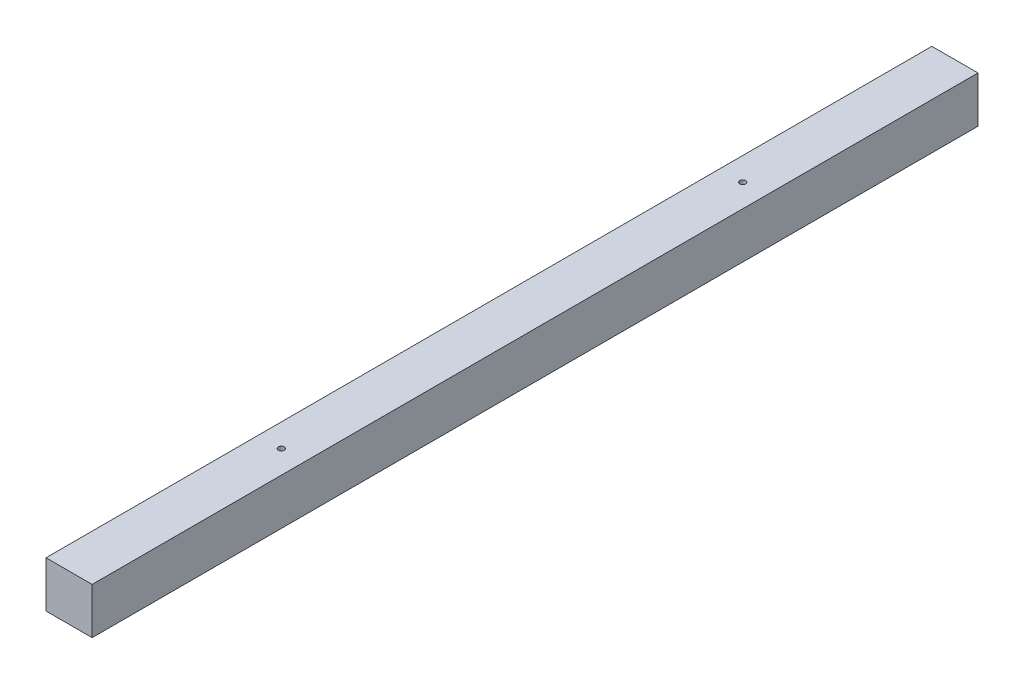
SolidWorks part; units mm, degrees
ref_plane "Płaszczyzna przednia" through (0, 0, 0) normal (0, 0, 1) x (1, 0, 0)
ref_plane "Płaszczyzna górna" through (0, 0, 0) normal (0, 1, 0) x (1, 0, 0)
ref_plane "Płaszczyzna prawa" through (0, 0, 0) normal (1, 0, 0) x (0, 0, -1)
sketch "Szkic1" plane through (0, 0, 0) normal (0, 0, 1) x (1, 0, 0)
  line L1 (0, 0) -> (25, 0)
  line L2 (0, 0) -> (0, 25)
  line L3 (0, 25) -> (25, 25)
  line L4 (25, 0) -> (25, 25)
  dimension "D1" = 25
extrude "Dodanie-wyciągnięcie1" add sketch "Szkic1" along normal blind 480
sketch "Szkic2" plane through (0, 25, 0) normal (0, 1, 0) x (1, 0, 0)
  line L0 (25, 0) -> (0, 0) construction
  line L1 (0, -480) -> (0, 0) construction
  line L2 (25, -480) -> (25, 0) construction
  line L3 (0, -240) -> (25, -240) construction
  circle A0 centre (12.5, -115) radius 1.6
  circle A1 centre (12.5, -365) radius 1.6
  dimension "D1" = 3.2
  dimension "D2" = 115
  dimension "D3" = 12.5
hole_wizard "Otwór pod śrubę M31" positions "Szkic3" profile "Szkic5" hole size "M3" standard "Ansi Metric"
sketch "Szkic3" plane through (0, 25, 0) normal (0, 1, 0) x (1, 0, 0)
  point P0 (12.5, -115)
  point P3 (12.5, -365)
sketch "Szkic5" plane through (12.5, 25, 115) normal (1, 0, 0) x (0, 0, 1)
  line L0 (0, 0) -> (0, 10.9614)
  line L1 (0, 10.9614) -> (1.6, 10)
  line L2 (1.6, 10) -> (1.6, 0)
  line L5 (1.6, 0) -> (0, 0)
  line L10 (0, 10.9614) -> (-1.6, 10) construction
  line L11 (0, -6.35) -> (0, 107.95) construction
  dimension "Œrednica otworu" = 3.2
  dimension "G³êbokoœæ otworu" = 10
  dimension "K¹t wiert³a" = 118
